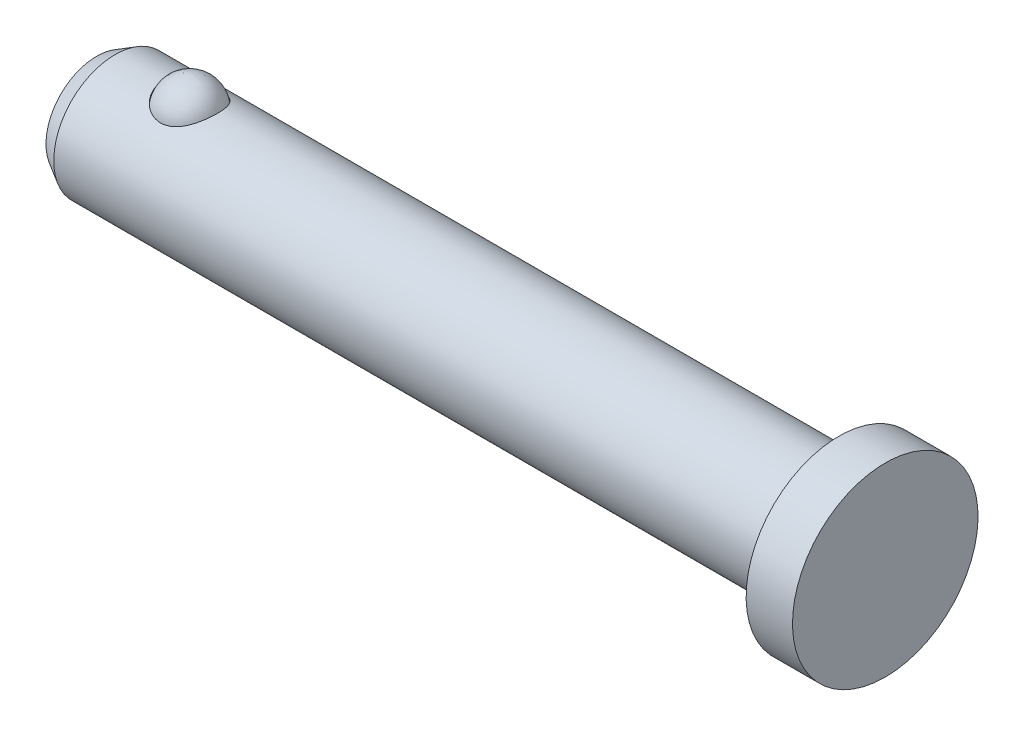
SolidWorks part; units mm, degrees
other "Imported1"
other "Imported2" parameters "D1"=138.0715, "Length"=138.0715, "Usable Length"=107.0085, "Head Height"=13.3603, "Head Diameter"=9.525, "Diameter"=6.2992, "Shaft Length"=38.1, "Ball Height"=7.2644, "Ball Width"=3.1496, "D2"=54.5332, "F"=55.499, "D10"=11.2649, "D11"=5.3256, "D4"=6.8632, "K"=3.175, "A"=19.0119, "B"=7.112, "D"=21.59, "E"=9.525, "D3"=24.257, "H"=41.275, "D5"=24.257, "Useable Length"=25.4, "D6"=0.9873, "D7"=3.8918, "D8"=4.5254, "D9"=5.5856, "G"=64.77, "D12"=34.036, "C"=6.8932, "A1"=15, "D13"=1.6682, "J"=3.048, "D14"=90, "D15"=34.5361, "Head Dia"=9.525
ref_plane "Front" through (0, 0, 0) normal (0, 0, 1) x (1, 0, 0)
ref_plane "Top" through (0, 0, 0) normal (0, 1, 0) x (1, 0, 0)
ref_plane "Right" through (0, 0, 0) normal (1, 0, 0) x (0, 0, -1)
sketch "Sketch4" plane through (0, 0, 0) normal (0, 0, 1) x (1, 0, 0)
  line L0 (-15.4654, -3.1496) -> (-15.4654, 4.1148) construction
  line L1 (20.2406, -3.1496) -> (-20.2406, -3.1496) construction
  line L2 (20.2406, -3.1496) -> (20.2406, 3.1496) construction
  line L3 (20.2406, 3.1496) -> (-20.2406, 3.1496) construction
  line L4 (-20.2406, -3.1496) -> (-20.2406, 3.1496) construction
  line L5 (20.2406, -3.1496) -> (-20.2406, 3.1496) construction
  line L6 (20.2406, 3.1496) -> (-20.2406, -3.1496) construction
  line L7 (20.2406, 4.7625) -> (17.8594, 4.7625)
  line L8 (20.2406, 4.7625) -> (20.2406, -4.7625)
  line L9 (20.2406, -4.7625) -> (17.8594, -4.7625)
  line L10 (17.8594, 4.7625) -> (17.8594, -4.7625)
  line L11 (20.2406, 4.7625) -> (17.8594, -4.7625) construction
  line L12 (20.2406, -4.7625) -> (17.8594, 4.7625) construction
  line L13 (-13.8906, 3.1496) -> (-17.0402, 3.1496) construction
  point P0 (0, 0)
  point P6 (-13.8906, 3.1496)
  point P12 (19.05, 0)
  point P17 (-15.4654, 3.1496)
  dimension "Head Height" = 2.3813
sketch "Sketch1" plane through (0, 0, 0) normal (0, 0, 1) x (1, 0, 0)
  line L0 (20.2406, 4.7625) -> (17.8594, 4.7625)
  line L1 (17.8594, 3.1496) -> (17.8594, 4.7625)
  line L4 (20.2406, 4.7625) -> (20.2406, 0)
  line L5 (20.2406, 4.7625) -> (20.2406, -4.7625) construction
  line L6 (17.8594, 4.7625) -> (17.8594, -4.7625) construction
  line L9 (20.2406, 4.7625) -> (17.8594, 4.7625) construction
  line L13 (-20.2406, -3.1496) -> (-20.2406, 3.1496) construction
  line L16 (17.8594, 3.1496) -> (-19.2957, 3.1496)
  line L17 (-20.2406, 3.1496) -> (-20.2406, 2.6041) construction
  line L19 (-19.2957, 3.1496) -> (-20.2406, 3.1496) construction
  line L22 (-20.2406, -3.1496) -> (-19.2957, -3.1496) construction
  line L24 (-20.2406, 0) -> (20.2406, 0)
  line L26 (-15.4654, -3.1496) -> (-15.4654, 4.1148) construction
  line L27 (20.2406, -3.1496) -> (-20.2406, 3.1496) construction
  line L29 (-20.2406, 0) -> (-20.2406, -2.6041) construction
  line L36 (17.8594, 0) -> (17.8594, 3.1496) construction
  line L37 (-20.2406, 2.6041) -> (-20.2406, 0)
  line L38 (-19.2957, -3.1496) -> (20.2406, -3.1496) construction
  line L39 (-20.2406, -2.6041) -> (-20.2406, -3.1496) construction
  line L40 (-19.2957, 3.1496) -> (-20.2406, 2.6041)
  line L42 (-19.2957, -3.1496) -> (-20.2406, -2.6041) construction
  line L43 (-19.2957, 3.1496) -> (-19.2957, -3.1496) construction
  circle A0 centre (-15.4654, 2.6366) radius 1.4782 construction
  point P4 (20.2406, 2.3813)
  point P26 (-16.9437, 2.6366)
  point P35 (-15.4654, 3.1496)
  dimension "D1" = 30
  dimension "D2" = 0.9449
revolve "Revolve1" add sketch "Sketch1" angle 360 about L24
sketch "Sketch2" plane through (0, 0, 0) normal (0, 0, 1) x (1, 0, 0)
  line L0 (-13.9618, 2.6366) -> (-16.9691, 2.6366)
  line L1 (-15.4654, 4.1148) -> (-15.4654, 4.1402) construction
  line L2 (-13.9618, 2.6366) -> (-10.9545, 2.6366) construction
  circle A1 centre (-15.4654, 2.6366) radius 1.4782 construction
  arc A2 (-16.9691, 2.6366) -> (-13.9618, 2.6366) centre (-15.4654, 2.6366) cw
  circle A4 centre (-15.4654, 2.6366) radius 1.4782 construction
  dimension "D1" = 0.0254
revolve "Cut-Revolve1" cut sketch "Sketch2" angle 360 about L2
sketch "Sketch3" plane through (0, 0, 0) normal (0, 0, 1) x (1, 0, 0)
  line L0 (-13.9872, 2.6366) -> (-16.9437, 2.6366)
  line L1 (-13.9872, 2.6366) -> (-11.0307, 2.6366) construction
  arc A1 (-13.9872, 2.6366) -> (-16.9437, 2.6366) centre (-15.4654, 2.6366) ccw
  circle A2 centre (-15.4654, 2.6366) radius 1.4782 construction
  point P5 (-13.9872, 2.6366)
revolve "Revolve2" add sketch "Sketch3" angle 360 about L1
equation "\"Ball Width@Sketch4\"=\"Diameter@Sketch4\"*.5"
equation "\"D2@Sketch1\"= \"Diameter@Sketch4\" * .15"
